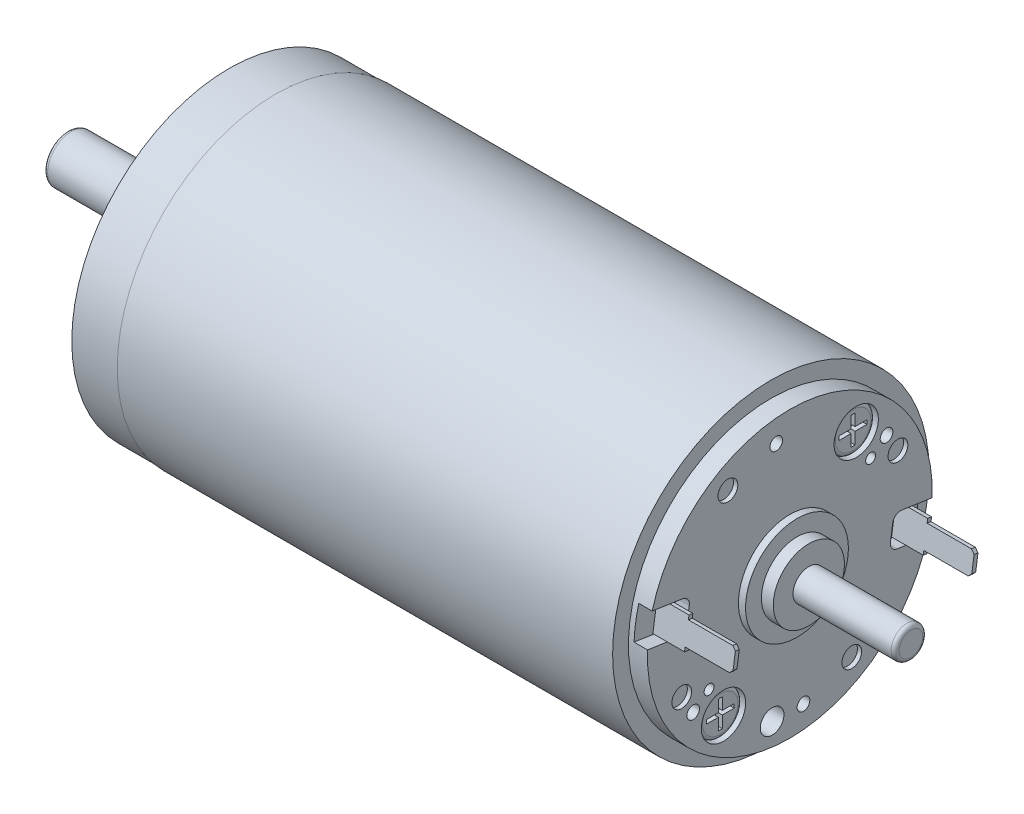
SolidWorks part; units mm, degrees
ref_plane "Front Plane" through (0, 0, 0) normal (0, 0, 1) x (1, 0, 0)
ref_plane "Top Plane" through (0, 0, 0) normal (0, 1, 0) x (1, 0, 0)
ref_plane "Right Plane" through (0, 0, 0) normal (1, 0, 0) x (0, 0, -1)
sketch "Sketch1" plane through (0, 0, 0) normal (0, 0, 1) x (1, 0, 0)
  line L0 (6, 20) -> (6, 0)
  line L1 (6, 0) -> (68.6, 0)
  line L2 (68.6, 0) -> (68.6, 20)
  line L3 (68.6, 20) -> (6, 20)
  line L4 (6, 0) -> (68.6, 0) construction
revolve "Revolve1" add sketch "Sketch1" angle 360 about L4
sketch "Sketch2" plane through (68.6, 0, 0) normal (1, 0, 0) x (0, 0, -1)
  circle A0 centre (0, 0) radius 18
extrude "Boss-Extrude1" add sketch "Sketch2" along normal blind 2.4
sketch "Sketch3" plane through (71, 0, 0) normal (1, 0, 0) x (0, 0, -1)
  line L0 (17.9877, -0.6661) -> (13.1528, 0.0565)
  line L1 (13.1528, 0.0565) -> (12.5616, -3.8996)
  line L2 (12.5616, -3.8996) -> (17.3964, -4.6221)
  arc A0 (17.3964, -4.6221) -> (17.9877, -0.6661) centre (0, 0) ccw
extrude "Cut-Extrude1" cut sketch "Sketch3" against normal blind 1.7
sketch "Sketch4" plane through (69.3, 0, 0) normal (1, 0, 0) x (0, 0, -1)
  line L0 (15.0489, -4.1702) -> (14.5544, -4.0963)
  line L1 (14.5544, -4.0963) -> (15.1161, -0.338)
  line L2 (15.1161, -0.338) -> (15.6106, -0.4119)
  line L3 (15.6106, -0.4119) -> (15.0489, -4.1702)
extrude "Boss-Extrude2" add sketch "Sketch4" along normal blind 10
sketch "Sketch5" plane through (0, -2.2171, -14.8352) normal (0, 0.1478, 0.989) x (1, 0, 0)
  line L0 (73.3, 1.4) -> (79.3, 1.4)
  line L1 (79.3, 1.4) -> (79.3, 1.9)
  line L2 (79.3, 1.9) -> (73.3, 1.9)
  line L3 (73.3, 1.9) -> (73.3, 1.4)
extrude "Cut-Extrude2" cut sketch "Sketch5" against normal through all
sketch "Sketch6" plane through (0, -2.2171, -14.8352) normal (0, 0.1478, 0.989) x (1, 0, 0)
  line L0 (73.3, -1.4) -> (73.3, -1.9)
  line L1 (73.3, -1.9) -> (79.3, -1.9)
  line L2 (79.3, -1.9) -> (79.3, -1.4)
  line L3 (79.3, -1.4) -> (73.3, -1.4)
extrude "Cut-Extrude3" cut sketch "Sketch6" against normal through all
sketch "Sketch7" plane through (71, 0, 0) normal (1, 0, 0) x (0, 0, -1)
  line L0 (-17.9877, 0.6661) -> (-13.1528, -0.0565)
  line L1 (-13.1528, -0.0565) -> (-12.5616, 3.8996)
  line L2 (-12.5616, 3.8996) -> (-17.3964, 4.6221)
  arc A0 (-17.3964, 4.6221) -> (-17.9877, 0.6661) centre (0, 0) ccw
extrude "Cut-Extrude4" cut sketch "Sketch7" against normal blind 1.7
sketch "Sketch8" plane through (69.3, 0, 0) normal (1, 0, 0) x (0, 0, -1)
  line L0 (-15.0489, 4.1702) -> (-14.5544, 4.0963)
  line L1 (-14.5544, 4.0963) -> (-15.1161, 0.338)
  line L2 (-15.1161, 0.338) -> (-15.6106, 0.4119)
  line L3 (-15.6106, 0.4119) -> (-15.0489, 4.1702)
extrude "Boss-Extrude3" add sketch "Sketch8" along normal blind 10
sketch "Sketch9" plane through (0, 2.2171, 14.8352) normal (0, -0.1478, -0.989) x (-1, 0, 0)
  line L0 (-79.3, -1.9) -> (-73.3, -1.9)
  line L1 (-73.3, -1.9) -> (-73.3, -1.4)
  line L2 (-73.3, -1.4) -> (-79.3, -1.4)
  line L3 (-79.3, -1.4) -> (-79.3, -1.9)
extrude "Cut-Extrude5" cut sketch "Sketch9" against normal through all
sketch "Sketch10" plane through (0, 2.2171, 14.8352) normal (0, -0.1478, -0.989) x (-1, 0, 0)
  line L0 (-79.3, 1.9) -> (-79.3, 1.4)
  line L1 (-79.3, 1.4) -> (-73.3, 1.4)
  line L2 (-73.3, 1.4) -> (-73.3, 1.9)
  line L3 (-73.3, 1.9) -> (-79.3, 1.9)
extrude "Cut-Extrude6" cut sketch "Sketch10" against normal through all
sketch "Sketch11" plane through (6, 0, 0) normal (-1, 0, 0) x (0, 0, 1)
  circle A0 centre (0, 0) radius 19.9
extrude "Boss-Extrude4" add sketch "Sketch11" along normal blind 5.85
sketch "Sketch12" plane through (0.15, 0, 0) normal (-1, 0, 0) x (0, 0, 1)
  circle A0 centre (0, 0) radius 18.5
extrude "Boss-Extrude5" add sketch "Sketch12" along normal blind 0.15
sketch "Sketch13" plane through (0, 0, 0) normal (-1, 0, 0) x (0, 0, 1)
  circle A0 centre (0, 0) radius 8
extrude "Boss-Extrude6" add sketch "Sketch13" along normal blind 1.4
sketch "Sketch14" plane through (-1.4, 0, 0) normal (-1, 0, 0) x (0, 0, 1)
  circle A0 centre (0, 0) radius 4.5
extrude "Boss-Extrude7" add sketch "Sketch14" along normal blind 2.15
sketch "Sketch15" plane through (-3.55, 0, 0) normal (-1, 0, 0) x (0, 0, 1)
  circle A0 centre (0, 0) radius 3
extrude "Boss-Extrude8" add sketch "Sketch15" along normal blind 16.75
sketch "Sketch16" plane through (71, 0, 0) normal (1, 0, 0) x (0, 0, -1)
  circle A0 centre (0, 0) radius 6.5
extrude "Boss-Extrude9" add sketch "Sketch16" along normal blind 0.9
sketch "Sketch17" plane through (71.9, 0, 0) normal (1, 0, 0) x (0, 0, -1)
  circle A0 centre (0, 0) radius 4.5
extrude "Boss-Extrude10" add sketch "Sketch17" along normal blind 1.5
sketch "Sketch18" plane through (73.4, 0, 0) normal (1, 0, 0) x (0, 0, -1)
  circle A0 centre (0, 0) radius 2
extrude "Boss-Extrude11" add sketch "Sketch18" along normal blind 12.9
hole_wizard "Ø5.6 (5.6) Diameter Hole1" positions "Sketch20" profile "Sketch19" hole size "Ø5.6" standard "ANSI Metric"
sketch "Sketch20" plane through (71, 0, 0) normal (1, 0, 0) x (0, 0, -1)
  point P0 (8.387, 11.3344)
sketch "Sketch19" plane through (71, 11.3344, -8.387) normal (0, 1, 0) x (0, 0, -1)
  line L0 (0, 0) -> (0, 2.4)
  line L1 (0, 2.4) -> (2.8, 2.4)
  line L2 (2.8, 2.4) -> (2.8, 0)
  line L5 (2.8, 0) -> (0, 0)
  line L10 (0, 2.4) -> (-2.8, 2.4) construction
  line L11 (0, -6.35) -> (0, 107.95) construction
  dimension "Hole Dia." = 5.6
  dimension "Hole Depth" = 2.4
  dimension "Drill Angle" = 180
sketch "Sketch21" plane through (68.6, 0, 0) normal (1, 0, 0) x (0, 0, -1)
  circle A0 centre (8.387, 11.3344) radius 2.75
extrude "Boss-Extrude12" add sketch "Sketch21" along normal blind 2
sketch "Sketch22" plane through (70.6, 0, 0) normal (1, 0, 0) x (0, 0, -1)
  line L0 (8.137, 13.0844) -> (8.137, 11.5844)
  line L1 (8.137, 11.5844) -> (6.637, 11.5844)
  line L2 (6.637, 11.5844) -> (6.637, 11.0844)
  line L3 (6.637, 11.0844) -> (8.137, 11.0844)
  line L4 (8.137, 11.0844) -> (8.137, 9.5844)
  line L5 (8.137, 9.5844) -> (8.637, 9.5844)
  line L6 (8.637, 9.5844) -> (8.637, 11.0844)
  line L7 (8.637, 11.0844) -> (10.137, 11.0844)
  line L8 (10.137, 11.0844) -> (10.137, 11.5844)
  line L9 (10.137, 11.5844) -> (8.637, 11.5844)
  line L10 (8.637, 11.5844) -> (8.637, 13.0844)
  line L11 (8.637, 13.0844) -> (8.137, 13.0844)
extrude "Cut-Extrude7" cut sketch "Sketch22" against normal blind 0.86
hole_wizard "Ø5.6 (5.6) Diameter Hole2" positions "Sketch24" profile "Sketch23" hole size "Ø5.6" standard "ANSI Metric"
sketch "Sketch24" plane through (71, 0, 0) normal (1, 0, 0) x (0, 0, -1)
  point P0 (-8.387, -11.3344)
sketch "Sketch23" plane through (71, -11.3344, 8.387) normal (0, 1, 0) x (0, 0, -1)
  line L0 (0, 0) -> (0, 2.4)
  line L1 (0, 2.4) -> (2.8, 2.4)
  line L2 (2.8, 2.4) -> (2.8, 0)
  line L5 (2.8, 0) -> (0, 0)
  line L10 (0, 2.4) -> (-2.8, 2.4) construction
  line L11 (0, -6.35) -> (0, 107.95) construction
  dimension "Hole Dia." = 5.6
  dimension "Hole Depth" = 2.4
  dimension "Drill Angle" = 180
sketch "Sketch25" plane through (68.6, 0, 0) normal (1, 0, 0) x (0, 0, -1)
  circle A0 centre (-8.387, -11.3344) radius 2.75
extrude "Boss-Extrude13" add sketch "Sketch25" along normal blind 2
sketch "Sketch26" plane through (70.6, 0, 0) normal (1, 0, 0) x (0, 0, -1)
  line L0 (-8.637, -9.5844) -> (-8.637, -11.0844)
  line L1 (-8.637, -11.0844) -> (-10.137, -11.0844)
  line L2 (-10.137, -11.0844) -> (-10.137, -11.5844)
  line L3 (-10.137, -11.5844) -> (-8.637, -11.5844)
  line L4 (-8.637, -11.5844) -> (-8.637, -13.0844)
  line L5 (-8.637, -13.0844) -> (-8.137, -13.0844)
  line L6 (-8.137, -13.0844) -> (-8.137, -11.5844)
  line L7 (-8.137, -11.5844) -> (-6.637, -11.5844)
  line L8 (-6.637, -11.5844) -> (-6.637, -11.0844)
  line L9 (-6.637, -11.0844) -> (-8.137, -11.0844)
  line L10 (-8.137, -11.0844) -> (-8.137, -9.5844)
  line L11 (-8.137, -9.5844) -> (-8.637, -9.5844)
extrude "Cut-Extrude8" cut sketch "Sketch26" against normal blind 0.86
hole_wizard "Ø3.0 (3) Diameter Hole1" positions "Sketch28" profile "Sketch27" hole size "Ø3.0" standard "ANSI Metric"
sketch "Sketch28" plane through (71, 0, 0) normal (1, 0, 0) x (0, 0, -1)
  point P0 (-2.243, -15.0348)
sketch "Sketch27" plane through (71, -15.0348, 2.243) normal (0, 1, 0) x (0, 0, -1)
  line L0 (0, 0) -> (0, 3.4)
  line L1 (0, 3.4) -> (1.5, 3.4)
  line L2 (1.5, 3.4) -> (1.5, 0)
  line L5 (1.5, 0) -> (0, 0)
  line L10 (0, 3.4) -> (-1.5, 3.4) construction
  line L11 (0, -6.35) -> (0, 107.95) construction
  dimension "Hole Dia." = 3
  dimension "Hole Depth" = 3.4
  dimension "Drill Angle" = 180
hole_wizard "Ø2.5 (2.5) Diameter Hole1" positions "Sketch30" profile "Sketch29" hole size "Ø2.5" standard "ANSI Metric"
sketch "Sketch30" plane through (71, 0, 0) normal (1, 0, 0) x (0, 0, -1)
  point P0 (7.8286, -13.0289)
  point P1 (-7.8286, 13.0289)
  point P2 (13.6617, 6.6632)
  point P3 (-13.6617, -6.6632)
sketch "Sketch29" plane through (71, -13.0289, -7.8286) normal (0, 1, 0) x (0, 0, -1)
  line L0 (0, 0) -> (0, 0.54)
  line L1 (0, 0.54) -> (1.25, 0.54)
  line L2 (1.25, 0.54) -> (1.25, 0)
  line L5 (1.25, 0) -> (0, 0)
  line L10 (0, 0.54) -> (-1.25, 0.54) construction
  line L11 (0, -6.35) -> (0, 107.95) construction
  dimension "Hole Dia." = 2.5
  dimension "Hole Depth" = 0.54
  dimension "Drill Angle" = 180
hole_wizard "Ø1.25 (1.25) Diameter Hole1" positions "Sketch32" profile "Sketch31" hole size "Ø1.25" standard "ANSI Metric"
sketch "Sketch32" plane through (71, 0, 0) normal (1, 0, 0) x (0, 0, -1)
  point P0 (10.209, 7.5542)
  point P1 (-10.209, -7.5542)
sketch "Sketch31" plane through (71, 7.5542, -10.209) normal (0, 1, 0) x (0, 0, -1)
  line L0 (0, 0) -> (0, 4.1108)
  line L1 (0, 4.1108) -> (0.625, 3.75)
  line L2 (0.625, 3.75) -> (0.625, 0)
  line L5 (0.625, 0) -> (0, 0)
  line L10 (0, 4.1108) -> (-0.625, 3.75) construction
  line L11 (0, -6.35) -> (0, 107.95) construction
  dimension "Hole Dia." = 1.25
  dimension "Hole Depth" = 3.75
  dimension "Drill Angle" = 120
hole_wizard "Ø1.6 (1.6) Diameter Hole1" positions "Sketch34" profile "Sketch33" hole size "Ø1.6" standard "ANSI Metric"
sketch "Sketch34" plane through (71, 0, 0) normal (1, 0, 0) x (0, 0, -1)
  point P0 (-1.7207, 15.1023)
  point P1 (1.7207, -15.1023)
  point P2 (12.2186, 9.0413)
  point P3 (-12.2186, -9.0413)
sketch "Sketch33" plane through (71, 15.1023, 1.7207) normal (0, 1, 0) x (0, 0, -1)
  line L0 (0, 0) -> (0, 5.2619)
  line L1 (0, 5.2619) -> (0.8, 4.8)
  line L2 (0.8, 4.8) -> (0.8, 0)
  line L5 (0.8, 0) -> (0, 0)
  line L10 (0, 5.2619) -> (-0.8, 4.8) construction
  line L11 (0, -6.35) -> (0, 107.95) construction
  dimension "Hole Dia." = 1.6
  dimension "Hole Depth" = 4.8
  dimension "Drill Angle" = 120
hole_wizard "Ø2.5 (2.5) Diameter Hole2" positions "Sketch36" profile "Sketch35" hole size "Ø2.5" standard "ANSI Metric"
sketch "Sketch36" plane through (0, 0, 0) normal (-1, 0, 0) x (0, 0, 1)
  point P0 (0, 11)
  point P1 (9.5263, 5.5)
  point P2 (9.5263, -5.5)
  point P3 (0, -11)
  point P4 (-9.5263, -5.5)
  point P5 (-9.5263, 5.5)
sketch "Sketch35" plane through (0, 11, 0) normal (0, 1, 0) x (0, 0, 1)
  line L0 (0, 0) -> (0, 8.2217)
  line L1 (0, 8.2217) -> (1.25, 7.5)
  line L2 (1.25, 7.5) -> (1.25, 0)
  line L5 (1.25, 0) -> (0, 0)
  line L10 (0, 8.2217) -> (-1.25, 7.5) construction
  line L11 (0, -6.35) -> (0, 107.95) construction
  dimension "Hole Dia." = 2.5
  dimension "Hole Depth" = 7.5
  dimension "Drill Angle" = 120
hole_wizard "Ø2.8 (2.8) Diameter Hole1" positions "Sketch38" profile "Sketch37" hole size "Ø2.8" standard "ANSI Metric"
sketch "Sketch38" plane through (0, 0, 0) normal (-1, 0, 0) x (0, 0, 1)
  point P0 (0, 15)
sketch "Sketch37" plane through (0, 15, 0) normal (0, 1, 0) x (0, 0, 1)
  line L0 (0, 0) -> (0, 2.0083)
  line L1 (0, 2.0083) -> (1.4, 1.2)
  line L2 (1.4, 1.2) -> (1.4, 0)
  line L5 (1.4, 0) -> (0, 0)
  line L10 (0, 2.0083) -> (-1.4, 1.2) construction
  line L11 (0, -6.35) -> (0, 107.95) construction
  dimension "Hole Dia." = 2.8
  dimension "Hole Depth" = 1.2
  dimension "Drill Angle" = 120
chamfer "Chamfer1" distance 0.4 angle 45 4 edges at (79.3, 3.6387, 14.8756) (79.3, 0.8695, 15.2894) (79.3, -0.8695, -15.2894) (79.3, -3.6387, -14.8756)
fillet "Fillet1" radius 0.5 4 edges at (-20.3, 0, 3) (70.6, 11.3344, -11.137) (70.6, -11.3344, 5.637) (86.3, 0, -2)
fillet "Fillet2" radius 1 4 edges at (70.15, -3.8996, -12.5616) (70.15, 3.8996, 12.5616) (70.15, 0.0565, -13.1528) (70.15, -0.0565, 13.1528)
